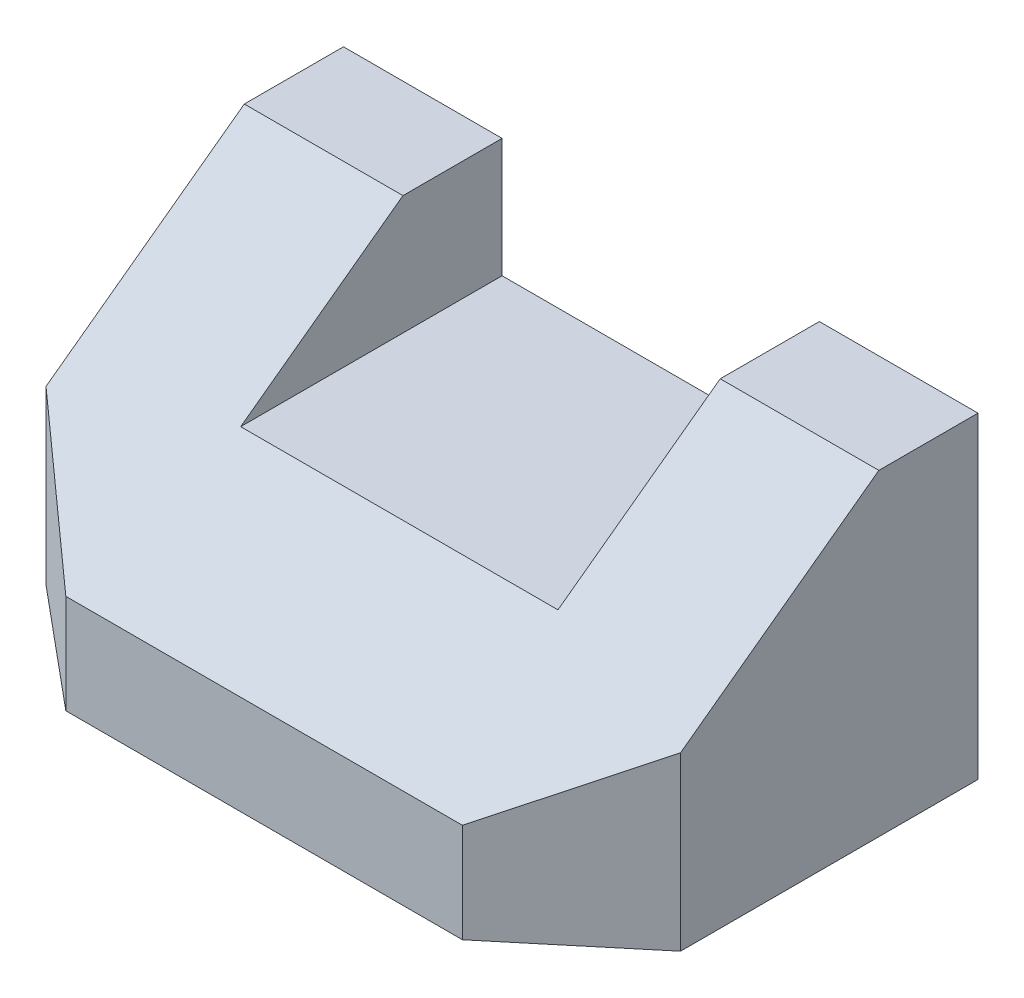
SolidWorks part; units mm, degrees
ref_plane "前基準面" through (0, 0, 0) normal (0, 0, 1) x (1, 0, 0)
ref_plane "上基準面" through (0, 0, 0) normal (0, 1, 0) x (1, 0, 0)
ref_plane "右基準面" through (0, 0, 0) normal (1, 0, 0) x (0, 0, -1)
sketch "草圖1" plane through (0, 0, 0) normal (1, 0, 0) x (0, 0, -1)
  line L0 (0, 0) -> (0, 10)
  line L1 (0, 10) -> (30, 32)
  line L2 (30, 32) -> (40, 32)
  line L3 (40, 32) -> (40, 0)
  line L4 (40, 0) -> (0, 0)
  dimension "D1" = 10
  dimension "D2" = 10
  dimension "D3" = 40
  dimension "D4" = 32
extrude "伸長1" add sketch "草圖1" along normal mid plane 64
sketch "草圖2" plane through (0, 0, 0) normal (0, 0, -1) x (-1, 0, 0)
  line L0 (-32, 32) -> (32, 32) construction
  line L1 (16, 32) -> (-16, 32)
  line L2 (16, 32) -> (16, 20)
  line L3 (16, 20) -> (-16, 20)
  line L4 (-16, 32) -> (-16, 20)
  line L5 (0, 0) -> (0, 20) construction
  line L6 (-32, 0) -> (32, 0) construction
  line L9 (32, 10) -> (32, 0) construction
  dimension "D1" = 12
  dimension "D2" = 16
extrude "伸長2" cut sketch "草圖2" along normal through all
sketch "草圖3" plane through (0, 0, 0) normal (0, -1, 0) x (1, 0, 0)
  line L0 (-32, -30) -> (-32, 0) construction
  line L1 (32, -30) -> (32, 0) construction
  line L2 (32, 0) -> (-32, 0) construction
  line L3 (-32, -10) -> (-32, 0)
  line L4 (32, -10) -> (32, 0)
  line L5 (32, 0) -> (20, 0)
  line L6 (20, 0) -> (32, -10)
  line L7 (-20, 0) -> (-32, -10)
  line L8 (-20, 0) -> (-32, 0)
  dimension "D1" = 10
  dimension "D2" = 10
  dimension "D3" = 12
  dimension "D4" = 12
extrude "伸長3" cut sketch "草圖3" against normal through all
